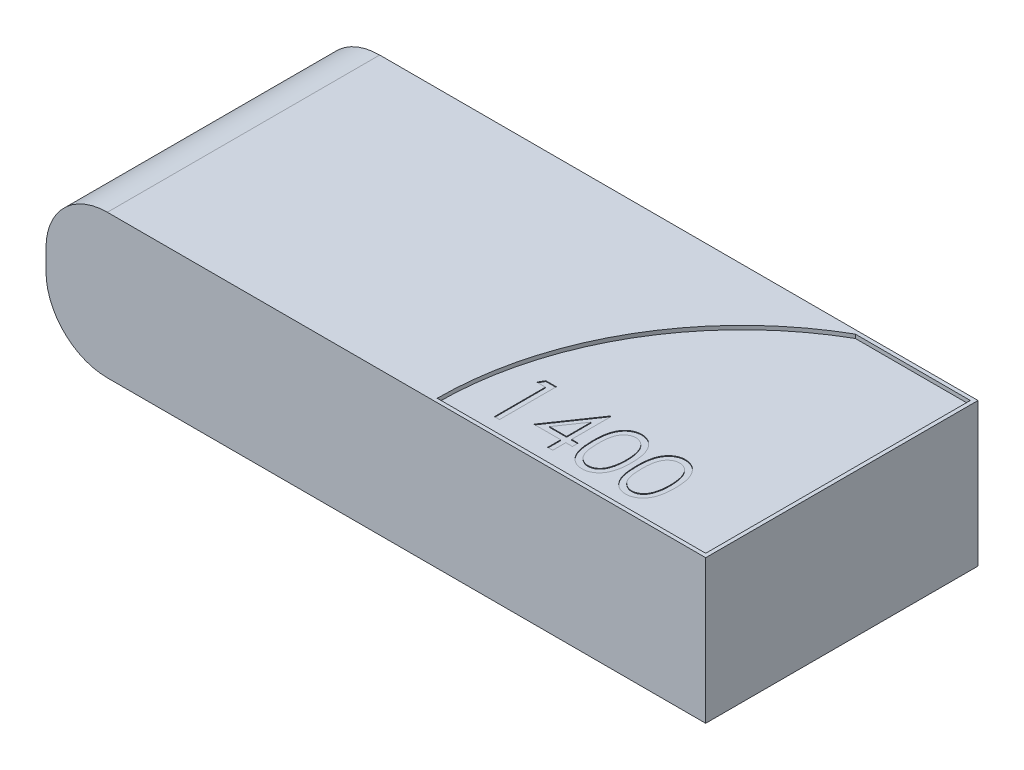
SolidWorks part; units mm, degrees
ref_plane "Alzado" through (0, 0, 0) normal (0, 0, 1) x (1, 0, 0)
ref_plane "Planta" through (0, 0, 0) normal (0, 1, 0) x (1, 0, 0)
ref_plane "Vista lateral" through (0, 0, 0) normal (1, 0, 0) x (0, 0, -1)
sketch "Croquis1" plane through (0, 0, 0) normal (0, 1, 0) x (1, 0, 0)
  line L1 (-43, 17.75) -> (43, 17.75)
  line L2 (-43, 17.75) -> (-43, -17.75)
  line L3 (-43, -17.75) -> (43, -17.75)
  line L4 (43, 17.75) -> (43, -17.75)
  line L5 (-43, 17.75) -> (43, -17.75) construction
  line L6 (-43, -17.75) -> (43, 17.75) construction
  point P0 (0, 0)
  dimension "D1" = 86
  dimension "D2" = 35.5
extrude "Saliente-Extruir1" add sketch "Croquis1" along normal blind 18.7
fillet "Redondeo2" radius 8 2 edges at (-43, 0, 0) (-43, 18.7, 0)
sketch "Croquis2" plane through (0, 18.7, 0) normal (0, 1, 0) x (1, 0, 0)
  line L0 (27.5, 17.25) -> (42.5, 17.25)
  line L1 (42.5, 17.25) -> (42.5, -17.25)
  line L2 (42.5, -17.25) -> (7.5, -17.25)
  line L4 (43, 17.75) -> (-35, 17.75) construction
  line L5 (43, -17.75) -> (43, 17.75) construction
  line L6 (-35, -17.75) -> (43, -17.75) construction
  arc A0 (7.5, -17.25) -> (27.5, 17.25) centre (47.2562, -17.25) cw
  point P5 (48.8147, -17.3236)
  point P12 (49.3617, -17.25)
  point P13 (8.0188, -17.75)
  dimension "D1" = 0.5
  dimension "D2" = 0.5
  dimension "D3" = 0.5
  dimension "D4" = 15
  dimension "D5" = 35
extrude "Cortar-Extruir1" cut sketch "Croquis2" against normal blind 0.5
sketch "Croquis3" plane through (0, 18.2, 0) normal (0, 1, 0) x (1, 0, 0)
  line L0 (12.0958, -7.6832) -> (13.4656, -7.6832)
  line L1 (13.4656, -7.6832) -> (13.4656, -15.0915)
  line L2 (13.4656, -15.0915) -> (12.8007, -15.0915)
  line L3 (12.8007, -15.0915) -> (12.8007, -8.443)
  line L4 (12.8007, -8.443) -> (11.661, -8.443)
  line L5 (11.661, -8.443) -> (12.0958, -7.6832)
  line L6 (20.264, -7.4932) -> (20.399, -7.4932)
  line L7 (20.399, -7.4932) -> (20.399, -12.6221)
  line L8 (20.399, -12.6221) -> (21.2538, -12.6221)
  line L9 (21.2538, -12.6221) -> (21.2538, -13.3819)
  line L10 (21.2538, -13.3819) -> (20.399, -13.3819)
  line L11 (20.399, -13.3819) -> (20.399, -15.0915)
  line L12 (20.399, -15.0915) -> (19.7342, -15.0915)
  line L13 (19.7342, -15.0915) -> (19.7342, -13.3819)
  line L14 (19.7342, -13.3819) -> (16.22, -13.3819)
  line L15 (16.22, -13.3819) -> (20.264, -7.4932)
  line L16 (19.7342, -12.6221) -> (19.7342, -9.4047)
  line L17 (19.7342, -9.4047) -> (17.5259, -12.6221)
  line L18 (17.5259, -12.6221) -> (19.7342, -12.6221)
  spline S0 degree 3 poles (21.9187, -11.3903) (21.9183, -11.1597) (21.9262, -10.8232) (21.9607, -10.3895) (21.9948, -10.095) (22.0364, -9.8212) (22.0919, -9.5688) (22.155, -9.3367) (22.2281, -9.1241) (22.3106, -8.9282) (22.4004, -8.7452) (22.5011, -8.5756) (22.6069, -8.4165) (22.7221, -8.2707) (22.8434, -8.136) (22.9755, -8.0155) (23.114, -7.9058) (23.2601, -7.8096) (23.4096, -7.7248) (23.5636, -7.6525) (23.7225, -7.5955) (23.8848, -7.5486) (24.1086, -7.5051) (24.2803, -7.4925) (24.3955, -7.4932) knots 0 0 0 0 0.133246 0.194313 0.251279 0.304513 0.354235 0.400481 0.443411 0.484015 0.523252 0.561042 0.5979 0.633518 0.668314 0.702496 0.736685 0.770293 0.803437 0.835913 0.86846 0.900847 0.933467 1 1 1 1
  spline S1 degree 3 poles (24.3955, -7.4932) (24.5127, -7.4929) (24.687, -7.5046) (24.9141, -7.5488) (25.0786, -7.5952) (25.2397, -7.6528) (25.3962, -7.7249) (25.5491, -7.8089) (25.6958, -7.9076) (25.8381, -8.0176) (25.9724, -8.142) (26.0987, -8.2795) (26.2187, -8.4286) (26.3289, -8.5922) (26.4338, -8.7674) (26.5277, -8.9573) (26.6182, -9.1588) (26.6962, -9.3774) (26.7667, -9.6118) (26.8236, -9.8649) (26.8709, -10.1353) (26.9076, -10.4241) (26.9443, -10.8439) (26.9505, -11.1687) (26.9525, -11.3903) knots 0 0 0 0 0.067194 0.099862 0.132567 0.165151 0.197913 0.231319 0.265083 0.299255 0.334399 0.369943 0.406284 0.444064 0.482998 0.523354 0.565537 0.609613 0.656391 0.705885 0.758325 0.813832 0.872795 1 1 1 1
  spline S2 degree 3 poles (26.9525, -11.3903) (26.9503, -11.611) (26.9447, -11.9343) (26.9071, -12.352) (26.8728, -12.6395) (26.8253, -12.9084) (26.7669, -13.1598) (26.702, -13.3946) (26.6219, -13.611) (26.5342, -13.812) (26.4389, -13.9997) (26.3367, -14.1757) (26.2254, -14.3387) (26.1068, -14.4898) (25.9782, -14.6263) (25.8435, -14.7515) (25.7008, -14.863) (25.5517, -14.9605) (25.3994, -15.0477) (25.2411, -15.1181) (25.0804, -15.1785) (24.9151, -15.2246) (24.6873, -15.2677) (24.5129, -15.2834) (24.3955, -15.2815) knots 0 0 0 0 0.126773 0.185516 0.240765 0.29298 0.34225 0.388919 0.432776 0.474628 0.514775 0.553606 0.591426 0.628028 0.663804 0.698984 0.733591 0.767628 0.801208 0.834264 0.866981 0.89972 0.932702 1 1 1 1
  spline S3 degree 3 poles (24.3955, -15.2815) (24.2804, -15.2821) (24.1086, -15.2698) (23.8855, -15.226) (23.724, -15.1807) (23.5659, -15.1252) (23.4133, -15.0529) (23.2645, -14.9697) (23.1199, -14.8748) (22.9823, -14.7662) (22.8509, -14.6461) (22.7289, -14.5114) (22.6154, -14.3643) (22.5075, -14.2062) (22.4082, -14.0349) (22.3164, -13.8511) (22.2325, -13.6536) (22.1581, -13.4395) (22.0924, -13.2063) (22.0405, -12.9521) (21.9961, -12.6788) (21.9603, -12.3853) (21.9265, -11.9539) (21.9182, -11.6195) (21.9187, -11.3903) knots 0 0 0 0 0.066622 0.099285 0.131361 0.163585 0.196104 0.228902 0.262158 0.295991 0.330218 0.36506 0.400951 0.43762 0.475708 0.515381 0.556414 0.599765 0.646424 0.696431 0.749782 0.806573 0.867436 1 1 1 1
  spline S4 degree 3 poles (22.5835, -11.3874) (22.5818, -11.5794) (22.5903, -11.8587) (22.6146, -12.2177) (22.6371, -12.4595) (22.6705, -12.6821) (22.708, -12.8869) (22.7536, -13.073) (22.8076, -13.2414) (22.869, -13.3952) (22.9362, -13.5383) (23.0083, -13.6724) (23.0889, -13.7963) (23.1768, -13.9104) (23.2699, -14.0167) (23.3716, -14.1115) (23.5124, -14.2253) (23.6982, -14.3426) (24.0072, -14.4785) (24.2544, -14.5217) (24.4178, -14.5217) knots 0 0 0 0 0.141584 0.205926 0.265301 0.320597 0.371817 0.41879 0.461699 0.502134 0.540804 0.578181 0.614297 0.649678 0.684299 0.718359 0.752081 0.817652 0.879722 1 1 1 1
  spline S5 degree 3 poles (24.4178, -14.5217) (24.5821, -14.5243) (24.8276, -14.4792) (25.1357, -14.3478) (25.3179, -14.2317) (25.4565, -14.1209) (25.5558, -14.0265) (25.6469, -13.9207) (25.7334, -13.8066) (25.8126, -13.682) (25.9109, -13.4989) (25.9711, -13.3514) (26.0072, -13.2498) knots 0 0 0 0 0.225394 0.339595 0.459675 0.521735 0.583926 0.648174 0.713881 0.781004 0.851451 1 1 1 1
  spline S6 degree 3 poles (26.0072, -13.2498) (26.0535, -13.1161) (26.119, -12.9096) (26.1793, -12.6229) (26.2208, -12.3955) (26.249, -12.1575) (26.28, -11.8209) (26.2874, -11.5626) (26.2877, -11.3874) knots 0 0 0 0 0.224542 0.342503 0.464324 0.590756 0.722227 1 1 1 1
  spline S7 degree 3 poles (26.2877, -11.3874) (26.2848, -11.2133) (26.2837, -10.9577) (26.2531, -10.6267) (26.2281, -10.3962) (26.1913, -10.1787) (26.1516, -9.9725) (26.0982, -9.78) (26.0412, -9.5982) (25.976, -9.4293) (25.9042, -9.2724) (25.8276, -9.1268) (25.7443, -8.9929) (25.6554, -8.8701) (25.5585, -8.7608) (25.4576, -8.6617) (25.3161, -8.5485) (25.131, -8.4332) (24.8268, -8.2924) (24.5794, -8.2552) (24.4178, -8.2531) knots 0 0 0 0 0.128486 0.188175 0.245106 0.299448 0.350823 0.399942 0.446672 0.491255 0.533376 0.573853 0.612526 0.649597 0.685532 0.720106 0.753838 0.818925 0.880493 1 1 1 1
  spline S8 degree 3 poles (24.4178, -8.2531) (24.2543, -8.2553) (24.0045, -8.292) (23.6974, -8.4327) (23.5127, -8.5489) (23.3712, -8.6597) (23.2715, -8.7557) (23.1781, -8.8608) (23.092, -8.976) (23.0114, -9.0997) (22.9373, -9.233) (22.8706, -9.3766) (22.8091, -9.5303) (22.7549, -9.6988) (22.7103, -9.8846) (22.669, -10.0887) (22.6398, -10.3125) (22.6139, -10.5544) (22.5907, -10.9146) (22.5815, -11.1943) (22.5835, -11.3874) knots 0 0 0 0 0.120883 0.182755 0.247811 0.281299 0.315088 0.349702 0.384857 0.420966 0.458511 0.497175 0.537602 0.580503 0.627468 0.678388 0.733983 0.793747 0.857714 1 1 1 1
  spline S9 degree 3 poles (27.6174, -11.3903) (27.617, -11.1597) (27.6249, -10.8232) (27.6594, -10.3895) (27.6935, -10.095) (27.7351, -9.8212) (27.7906, -9.5688) (27.8537, -9.3367) (27.9268, -9.1241) (28.0093, -8.9282) (28.0992, -8.7452) (28.1998, -8.5756) (28.3056, -8.4165) (28.4208, -8.2707) (28.5421, -8.136) (28.6742, -8.0155) (28.8127, -7.9058) (28.9588, -7.8096) (29.1083, -7.7248) (29.2623, -7.6525) (29.4212, -7.5955) (29.5835, -7.5486) (29.8073, -7.5051) (29.9791, -7.4925) (30.0943, -7.4932) knots 0 0 0 0 0.133246 0.194313 0.251279 0.304513 0.354235 0.400481 0.443411 0.484015 0.523252 0.561042 0.5979 0.633518 0.668314 0.702496 0.736685 0.770293 0.803437 0.835913 0.86846 0.900847 0.933467 1 1 1 1
  spline S10 degree 3 poles (30.0943, -7.4932) (30.2114, -7.4929) (30.3857, -7.5046) (30.6128, -7.5488) (30.7773, -7.5952) (30.9384, -7.6528) (31.0949, -7.7249) (31.2478, -7.8089) (31.3945, -7.9076) (31.5368, -8.0176) (31.6711, -8.142) (31.7974, -8.2795) (31.9174, -8.4286) (32.0276, -8.5922) (32.1325, -8.7674) (32.2264, -8.9573) (32.3169, -9.1588) (32.395, -9.3774) (32.4654, -9.6118) (32.5223, -9.8649) (32.5697, -10.1353) (32.6064, -10.4241) (32.6431, -10.8439) (32.6493, -11.1687) (32.6513, -11.3903) knots 0 0 0 0 0.067194 0.099862 0.132567 0.165151 0.197913 0.231319 0.265083 0.299255 0.334399 0.369943 0.406284 0.444064 0.482998 0.523354 0.565537 0.609613 0.656391 0.705885 0.758325 0.813832 0.872795 1 1 1 1
  spline S11 degree 3 poles (32.6513, -11.3903) (32.649, -11.611) (32.6435, -11.9343) (32.6058, -12.352) (32.5715, -12.6395) (32.524, -12.9084) (32.4656, -13.1598) (32.4007, -13.3946) (32.3206, -13.611) (32.233, -13.812) (32.1376, -13.9997) (32.0354, -14.1757) (31.9241, -14.3387) (31.8055, -14.4898) (31.677, -14.6263) (31.5422, -14.7515) (31.3995, -14.863) (31.2505, -14.9605) (31.0981, -15.0477) (30.9398, -15.1181) (30.7792, -15.1785) (30.6138, -15.2246) (30.386, -15.2677) (30.2116, -15.2834) (30.0943, -15.2815) knots 0 0 0 0 0.126773 0.185516 0.240765 0.29298 0.34225 0.388919 0.432776 0.474628 0.514775 0.553606 0.591426 0.628028 0.663804 0.698984 0.733591 0.767628 0.801208 0.834264 0.866981 0.89972 0.932702 1 1 1 1
  spline S12 degree 3 poles (30.0943, -15.2815) (29.9791, -15.2821) (29.8073, -15.2698) (29.5842, -15.226) (29.4227, -15.1807) (29.2646, -15.1252) (29.112, -15.0529) (28.9632, -14.9697) (28.8187, -14.8748) (28.681, -14.7662) (28.5496, -14.6461) (28.4276, -14.5114) (28.3141, -14.3643) (28.2062, -14.2062) (28.107, -14.0349) (28.0152, -13.8511) (27.9312, -13.6536) (27.8568, -13.4395) (27.7911, -13.2063) (27.7392, -12.9521) (27.6948, -12.6788) (27.659, -12.3853) (27.6252, -11.9539) (27.6169, -11.6195) (27.6174, -11.3903) knots 0 0 0 0 0.066622 0.099285 0.131361 0.163585 0.196104 0.228902 0.262158 0.295991 0.330218 0.36506 0.400951 0.43762 0.475708 0.515381 0.556414 0.599765 0.646424 0.696431 0.749782 0.806573 0.867436 1 1 1 1
  spline S13 degree 3 poles (28.2822, -11.3874) (28.2805, -11.5794) (28.289, -11.8587) (28.3133, -12.2177) (28.3358, -12.4595) (28.3692, -12.6821) (28.4067, -12.8869) (28.4523, -13.073) (28.5063, -13.2414) (28.5678, -13.3952) (28.6349, -13.5383) (28.707, -13.6724) (28.7877, -13.7963) (28.8755, -13.9104) (28.9686, -14.0167) (29.0704, -14.1115) (29.2111, -14.2253) (29.397, -14.3426) (29.7059, -14.4785) (29.9531, -14.5217) (30.1165, -14.5217) knots 0 0 0 0 0.141584 0.205926 0.265301 0.320597 0.371817 0.41879 0.461699 0.502134 0.540804 0.578181 0.614297 0.649678 0.684299 0.718359 0.752081 0.817652 0.879722 1 1 1 1
  spline S14 degree 3 poles (30.1165, -14.5217) (30.2808, -14.5243) (30.5264, -14.4792) (30.8344, -14.3478) (31.0166, -14.2317) (31.1552, -14.1209) (31.2545, -14.0265) (31.3456, -13.9207) (31.4321, -13.8066) (31.5114, -13.682) (31.6097, -13.4989) (31.6698, -13.3514) (31.7059, -13.2498) knots 0 0 0 0 0.225394 0.339595 0.459675 0.521735 0.583926 0.648174 0.713881 0.781004 0.851451 1 1 1 1
  spline S15 degree 3 poles (31.7059, -13.2498) (31.7522, -13.1161) (31.8178, -12.9096) (31.8781, -12.6229) (31.9195, -12.3955) (31.9477, -12.1575) (31.9788, -11.8209) (31.9861, -11.5626) (31.9864, -11.3874) knots 0 0 0 0 0.224542 0.342503 0.464324 0.590756 0.722227 1 1 1 1
  spline S16 degree 3 poles (31.9864, -11.3874) (31.9835, -11.2133) (31.9824, -10.9577) (31.9518, -10.6267) (31.9268, -10.3962) (31.89, -10.1787) (31.8503, -9.9725) (31.7969, -9.78) (31.74, -9.5982) (31.6747, -9.4293) (31.6029, -9.2724) (31.5263, -9.1268) (31.443, -8.9929) (31.3541, -8.8701) (31.2573, -8.7608) (31.1563, -8.6617) (31.0149, -8.5485) (30.8297, -8.4332) (30.5255, -8.2924) (30.2781, -8.2552) (30.1165, -8.2531) knots 0 0 0 0 0.128486 0.188175 0.245106 0.299448 0.350823 0.399942 0.446672 0.491255 0.533376 0.573853 0.612526 0.649597 0.685532 0.720106 0.753838 0.818925 0.880493 1 1 1 1
  spline S17 degree 3 poles (30.1165, -8.2531) (29.953, -8.2553) (29.7032, -8.292) (29.3961, -8.4327) (29.2114, -8.5489) (29.0699, -8.6597) (28.9703, -8.7557) (28.8768, -8.8608) (28.7907, -8.976) (28.7101, -9.0997) (28.6361, -9.233) (28.5694, -9.3766) (28.5078, -9.5303) (28.4537, -9.6988) (28.409, -9.8846) (28.3678, -10.0887) (28.3386, -10.3125) (28.3126, -10.5544) (28.2894, -10.9146) (28.2803, -11.1943) (28.2822, -11.3874) knots 0 0 0 0 0.120883 0.182755 0.247811 0.281299 0.315088 0.349702 0.384857 0.420966 0.458511 0.497175 0.537602 0.580503 0.627468 0.678388 0.733983 0.793747 0.857714 1 1 1 1
extrude "Cortar-Extruir2" cut sketch "Croquis3" against normal blind 0.1
